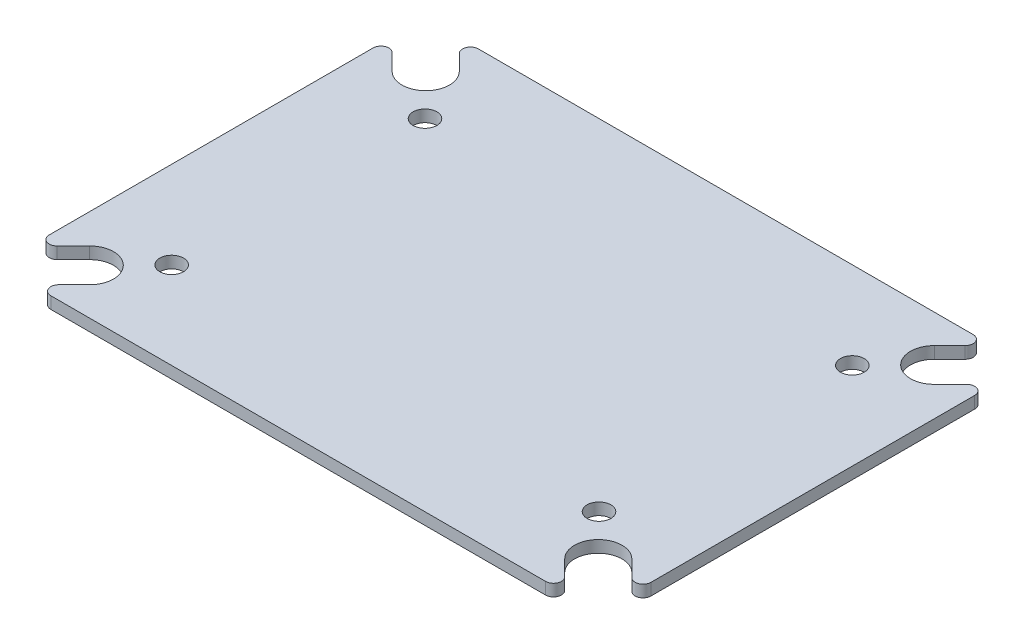
SolidWorks part; units mm, degrees
ref_plane "Front Plane" through (0, 0, 0) normal (0, 0, 1) x (1, 0, 0)
ref_plane "Top Plane" through (0, 0, 0) normal (0, 1, 0) x (1, 0, 0)
ref_plane "Right Plane" through (0, 0, 0) normal (1, 0, 0) x (0, 0, -1)
sketch "Sketch1" plane through (0, 0, 0) normal (0, 1, 0) x (1, 0, 0)
  line L0 (8.0067, -9.9027) -> (11.0125, -13.0012) construction
  line L1 (6.755, -2) -> (69.245, -2)
  line L2 (0, -8.5549) -> (0, -49.4451)
  line L3 (6.755, -56) -> (69.245, -56)
  line L4 (76, -8.5549) -> (76, -49.4451)
  line L5 (8.0037, -5.6591) -> (6.0486, -3.7078)
  line L6 (3.7631, -9.9037) -> (1.7071, -7.8478)
  line L7 (72.2369, -9.9037) -> (74.2929, -7.8478)
  line L8 (67.9963, -5.6591) -> (69.9514, -3.7078)
  line L9 (72.2369, -48.0963) -> (74.2929, -50.1522)
  line L10 (67.9963, -52.3409) -> (69.9514, -54.2922)
  line L11 (3.7631, -48.0963) -> (1.7071, -50.1522)
  line L12 (38, 0) -> (38, -56) construction
  line L13 (8.0037, -52.3409) -> (6.0486, -54.2922)
  line L15 (0, -29) -> (78, -29) construction
  arc A0 (3.7631, -9.9037) -> (8.0037, -5.6591) centre (5.8844, -7.7824) ccw
  arc A1 (72.2369, -9.9037) -> (67.9963, -5.6591) centre (70.1156, -7.7824) cw
  arc A2 (72.2369, -48.0963) -> (67.9963, -52.3409) centre (70.1156, -50.2176) ccw
  arc A3 (3.7631, -48.0963) -> (8.0037, -52.3409) centre (5.8844, -50.2176) cw
  circle A4 centre (11.0125, -13.0012) radius 1.5
  circle A5 centre (64.9875, -13.0012) radius 1.5
  circle A6 centre (64.9875, -44.9988) radius 1.5
  circle A7 centre (11.0125, -44.9988) radius 1.5
  arc A8 (69.9514, -3.7078) -> (69.245, -2) centre (69.245, -3) ccw
  arc A9 (74.2929, -7.8478) -> (76, -8.5549) centre (75, -8.5549) cw
  arc A10 (74.2929, -50.1522) -> (76, -49.4451) centre (75, -49.4451) ccw
  arc A11 (69.9514, -54.2922) -> (69.245, -56) centre (69.245, -55) cw
  arc A12 (6.0486, -54.2922) -> (6.755, -56) centre (6.755, -55) ccw
  arc A13 (1.7071, -50.1522) -> (0, -49.4451) centre (1, -49.4451) cw
  arc A14 (0, -8.5549) -> (1.7071, -7.8478) centre (1, -8.5549) cw
  arc A15 (6.755, -2) -> (6.0486, -3.7078) centre (6.755, -3) ccw
  point P3 (72.0165, -2)
  point P11 (76, -5.7869)
  point P32 (71.6625, -2)
  point P36 (76, -6.1407)
  point P43 (76, -51.8593)
  point P44 (76, -52.2131)
  point P47 (72.0165, -56)
  point P48 (71.6625, -56)
  point P50 (3.9835, -56)
  point P52 (4.3375, -56)
  point P53 (0, -52.2131)
  point P56 (0, -5.7869)
  point P57 (0, -51.8593)
  point P59 (3.9835, -2)
  point P61 (0, -6.1407)
  point P64 (4.3375, -2)
  dimension "D6" = 26.9875
  dimension "D1" = 1
  dimension "D2" = 54
  dimension "D3" = 76
  dimension "D7" = 15.9988
extrude "Boss-Extrude1" add sketch "Sketch1" along normal blind 1.5
